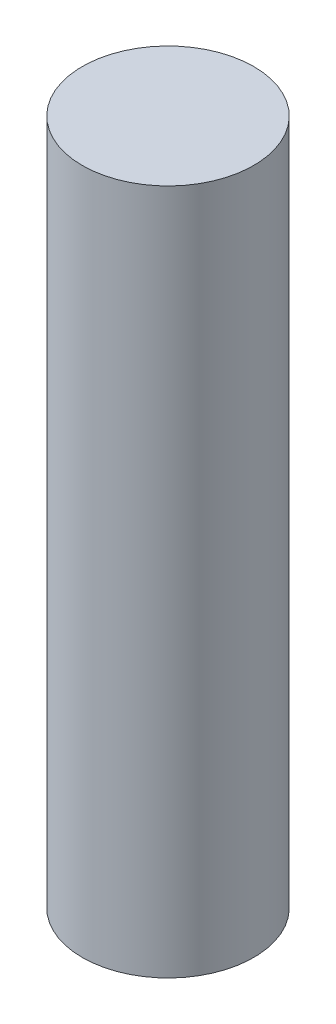
SolidWorks part; units mm, degrees
ref_plane "Front Plane" through (0, 0, 0) normal (0, 0, 1) x (1, 0, 0)
ref_plane "Top Plane" through (0, 0, 0) normal (0, 1, 0) x (1, 0, 0)
ref_plane "Right Plane" through (0, 0, 0) normal (1, 0, 0) x (0, 0, -1)
sketch "Sketch1" plane through (0, 0, 0) normal (0, 1, 0) x (1, 0, 0)
  circle A0 centre (0, 0) radius 3
  dimension "D1" = 6
extrude "Boss-Extrude1" add sketch "Sketch1" along normal blind 24
